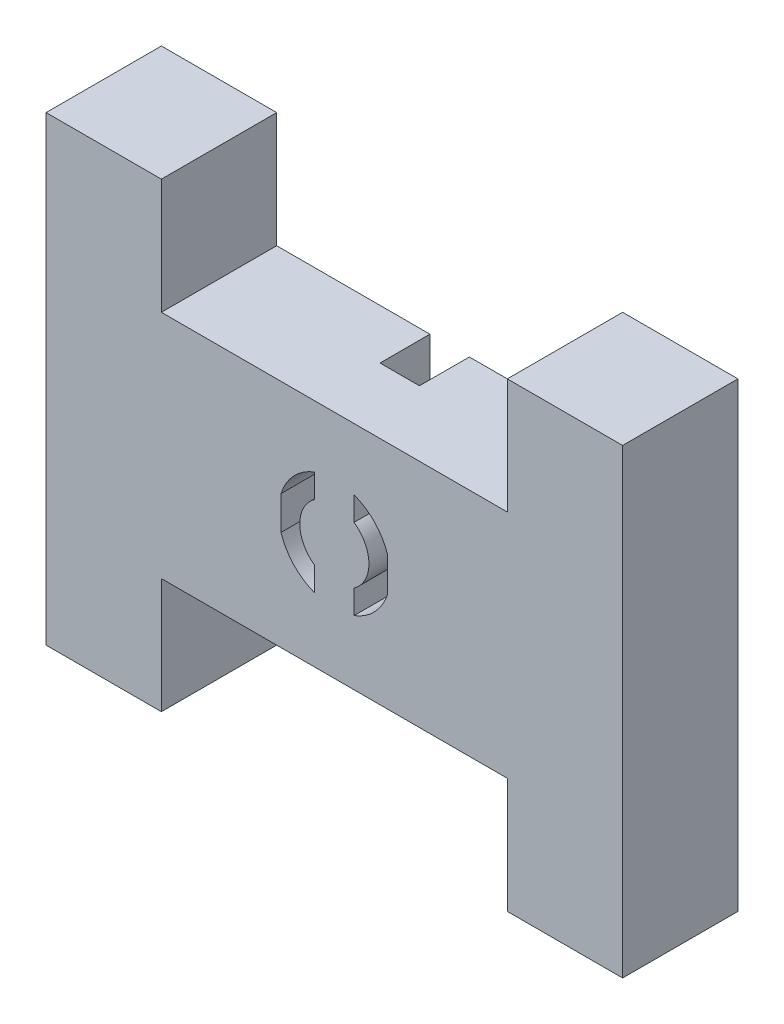
SolidWorks part; units mm, degrees
ref_plane "前视基准面" through (0, 0, 0) normal (0, 0, 1) x (1, 0, 0)
ref_plane "上视基准面" through (0, 0, 0) normal (0, 1, 0) x (1, 0, 0)
ref_plane "右视基准面" through (0, 0, 0) normal (1, 0, 0) x (0, 0, -1)
sketch "草图1" plane through (0, 0, 0) normal (0, 0, 1) x (1, 0, 0)
  line L1 (0, 0) -> (200, 0)
  line L2 (0, 0) -> (0, -200)
  line L3 (0, -200) -> (200, -200)
  line L4 (200, 0) -> (200, -200)
  dimension "D1" = 200
extrude "凸台-拉伸1" add sketch "草图1" along normal blind 100
sketch "草图2" plane through (0, 0, 0) normal (0, 0, -1) x (-1, 0, 0)
  line L0 (-146.25, -98.8742) -> (-146.25, -84.2732)
  line L1 (-146.25, -84.2732) -> (-146.25, -113.4751)
  line L2 (-100, 0) -> (-100, -98.8742) construction
  line L3 (-200, 0) -> (0, 0) construction
  line L4 (-53.75, -98.8742) -> (-146.25, -98.8742) construction
  line L5 (-53.75, -84.2732) -> (-53.75, -113.4751)
  circle A0 centre (-100, -98.8742) radius 48.5
  point P11 (0, 0)
  dimension "D1" = 97
  dimension "D2" = 92.5
extrude "切除-拉伸1" cut sketch "草图2" against normal blind 34.3 and the other way through all contours L5 A0 L0 L1
sketch "草图3" plane through (0, 0, 34.3) normal (0, 0, -1) x (-1, 0, 0)
  line L2 (-53.75, -113.4751) -> (-53.75, -84.2732)
  line L3 (-146.25, -84.2732) -> (-146.25, -113.4751)
  line L4 (-53.75, -113.4751) -> (-53.75, -84.2732)
  line L5 (-146.25, -84.2732) -> (-146.25, -113.4751)
  circle A0 centre (-100, -98.8742) radius 30
  arc A2 (-53.75, -84.2732) -> (-146.25, -84.2732) centre (-100, -98.8742) ccw
  arc A3 (-146.25, -113.4751) -> (-53.75, -113.4751) centre (-100, -98.8742) ccw
  arc A4 (-53.75, -84.2732) -> (-146.25, -84.2732) centre (-100, -98.8742) ccw
  arc A5 (-146.25, -113.4751) -> (-53.75, -113.4751) centre (-100, -98.8742) ccw
  dimension "D2" = 60
  dimension "D1" = 0
extrude "切除-拉伸2" cut sketch "草图3" against normal blind 9 contours A0
sketch "草图4" plane through (0, 0, 0) normal (0, 0, -1) x (-1, 0, 0)
  line L0 (0, -200) -> (-200, -200) construction
  line L1 (-117.1083, 2.2517) -> (-82.8917, 2.2517)
  line L2 (-117.1083, 2.2517) -> (-117.1083, -200)
  line L3 (-117.1083, -200) -> (-82.8917, -200)
  line L4 (-82.8917, 2.2517) -> (-82.8917, -200)
  line L5 (-117.1083, 2.2517) -> (-82.8917, -200) construction
  line L6 (-117.1083, -200) -> (-82.8917, 2.2517) construction
  circle A1 centre (-100, -98.8742) radius 30
  circle A2 centre (-100, -98.8742) radius 30
  point P9 (0, 0)
  line M3 (0, 0) -> (-200, 0)
  line M5 (-200, -200) -> (0, -200)
  arc M7 (-53.75, -113.4751) -> (-146.25, -113.4751) centre (-100, -98.8742) cw
  arc M9 (-146.25, -84.2732) -> (-53.75, -84.2732) centre (-100, -98.8742) cw
  dimension "D1" = 0
extrude "切除-拉伸3" cut sketch "草图4" against normal up to surface (43.3 mm away) contours L4 L2 M3 M9 | A2 L4 L2 M9 | L4 A2 L2 | A2 L2 L4 M7 | L4 L2 M7 M5 up to face at (70, -98.8742, 43.3)
sketch "草图6" plane through (0, 0, 100) normal (0, 0, 1) x (1, 0, 0)
  line L3 (82.8917, -74.2306) -> (82.8917, -53.4918)
  line L4 (0, 0) -> (0, -200)
  line L5 (0, -200) -> (200, -200)
  line L6 (200, -200) -> (200, 0)
  line L7 (200, 0) -> (0, 0)
  line L8 (0, 0) -> (0, -200)
  line L9 (0, -200) -> (200, -200)
  line L10 (200, -200) -> (200, 0)
  line L11 (200, 0) -> (0, 0)
  line L12 (82.8917, -144.2565) -> (82.8917, -123.5177)
  line L13 (53.75, -84.2732) -> (53.75, -113.4751)
  line L14 (82.8917, -74.2306) -> (82.8917, -53.4918)
  line L15 (82.8917, -144.2565) -> (82.8917, -123.5177)
  line L16 (53.75, -84.2732) -> (53.75, -113.4751)
  line L17 (117.1083, -53.4918) -> (117.1083, -74.2306)
  line L18 (146.25, -113.4751) -> (146.25, -84.2732)
  line L19 (117.1083, -123.5177) -> (117.1083, -144.2565)
  line L20 (117.1083, -53.4918) -> (117.1083, -74.2306)
  line L21 (146.25, -113.4751) -> (146.25, -84.2732)
  line L22 (117.1083, -123.5177) -> (117.1083, -144.2565)
  arc A3 (82.8917, -53.4918) -> (53.75, -84.2732) centre (100, -98.8742) ccw
  arc A4 (82.8917, -74.2306) -> (82.8917, -123.5177) centre (100, -98.8742) ccw
  arc A5 (53.75, -113.4751) -> (82.8917, -144.2565) centre (100, -98.8742) ccw
  arc A6 (82.8917, -53.4918) -> (53.75, -84.2732) centre (100, -98.8742) ccw
  arc A7 (82.8917, -74.2306) -> (82.8917, -123.5177) centre (100, -98.8742) ccw
  arc A8 (53.75, -113.4751) -> (82.8917, -144.2565) centre (100, -98.8742) ccw
  arc A9 (146.25, -84.2732) -> (117.1083, -53.4918) centre (100, -98.8742) ccw
  arc A10 (117.1083, -144.2565) -> (146.25, -113.4751) centre (100, -98.8742) ccw
  arc A11 (117.1083, -123.5177) -> (117.1083, -74.2306) centre (100, -98.8742) ccw
  arc A12 (146.25, -84.2732) -> (117.1083, -53.4918) centre (100, -98.8742) ccw
  arc A13 (117.1083, -144.2565) -> (146.25, -113.4751) centre (100, -98.8742) ccw
  arc A14 (117.1083, -123.5177) -> (117.1083, -74.2306) centre (100, -98.8742) ccw
  dimension "D1" = 0
  dimension "D2" = 0
  dimension "D3" = 0
extrude "切除-拉伸4" cut sketch "草图6" against normal blind 55 contours A6 L16 A8 L15 A7 L14 | L20 A14 L22 A13 L21 A12
sketch "草图7" plane through (0, 0, 34.3) normal (0, 0, -1) x (-1, 0, 0)
  line L6 (-117.1083, -74.2306) -> (-117.1083, -53.4918)
  line L7 (-146.25, -84.2732) -> (-146.25, -113.4751)
  line L8 (-117.1083, -144.2565) -> (-117.1083, -123.5177)
  line L9 (-117.1083, -74.2306) -> (-117.1083, -53.4918) construction
  line L10 (-146.25, -84.2732) -> (-146.25, -113.4751) construction
  line L11 (-117.1083, -144.2565) -> (-117.1083, -123.5177) construction
  circle A3 centre (-100, -98.8742) radius 42.5 construction
  circle A4 centre (-142.5, -98.8742) radius 1.75
  circle A5 centre (-130.052, -68.8221) radius 1.75
  arc A6 (-117.1083, -53.4918) -> (-146.25, -84.2732) centre (-100, -98.8742) ccw
  arc A7 (-146.25, -113.4751) -> (-117.1083, -144.2565) centre (-100, -98.8742) ccw
  arc A8 (-117.1083, -74.2306) -> (-117.1083, -123.5177) centre (-100, -98.8742) ccw
  arc A9 (-117.1083, -53.4918) -> (-146.25, -84.2732) centre (-100, -98.8742) ccw construction
  arc A10 (-146.25, -113.4751) -> (-117.1083, -144.2565) centre (-100, -98.8742) ccw construction
  arc A11 (-117.1083, -74.2306) -> (-117.1083, -123.5177) centre (-100, -98.8742) ccw construction
  circle A13 centre (-69.948, -68.8221) radius 1.75
  circle A14 centre (-57.5, -98.8742) radius 1.75
  circle A15 centre (-69.948, -128.9262) radius 1.75
  circle A17 centre (-130.052, -128.9262) radius 1.75
  circle A18 centre (-100, -56.3742) radius 1.75 [skipped]
  circle A19 centre (-100, -141.3742) radius 1.75 [skipped]
  point P29 (-100, -98.8742)
  dimension "D2" = 85
  dimension "D3" = 3.5
  dimension "D1" = 0
  dimension "D4" = 8
extrude "切除-拉伸7" cut sketch "草图7" against normal through all
sketch "草图9" plane through (0, 0, 0) normal (-1, 0, 0) x (0, 0, 1)
  line L4 (0, 0) -> (0, -200)
  line L5 (0, -200) -> (100, -200)
  line L6 (100, -200) -> (100, 0)
  line L7 (100, 0) -> (0, 0)
  line L8 (0, 0) -> (0, -200)
  line L9 (0, -200) -> (100, -200)
  line L10 (100, -200) -> (100, 0)
  line L11 (100, 0) -> (0, 0)
  dimension "D1" = 0
extrude "凸台-拉伸2" add sketch "草图9" along normal blind 150
sketch "草图10" plane through (200, 0, 0) normal (1, 0, 0) x (0, 0, -1)
  line L4 (0, -200) -> (0, 0)
  line L5 (0, 0) -> (-100, 0)
  line L6 (-100, 0) -> (-100, -200)
  line L7 (-100, -200) -> (0, -200)
  line L8 (0, -200) -> (0, 0)
  line L9 (0, 0) -> (-100, 0)
  line L10 (-100, 0) -> (-100, -200)
  line L11 (-100, -200) -> (0, -200)
  dimension "D1" = 0
extrude "凸台-拉伸3" add sketch "草图10" along normal blind 150
sketch "草图11" plane through (0, -200, 0) normal (0, -1, 0) x (1, 0, 0)
  line L0 (100, 43.3) -> (100, 150.463) construction
  line L1 (82.8917, 43.3) -> (117.1083, 43.3) construction
  line L2 (-150, 100) -> (350, 100) construction
  line L3 (-50, 100) -> (-150, 100)
  line L4 (-50, 100) -> (-50, 0)
  line L5 (-50, 0) -> (-150, 0)
  line L6 (-150, 100) -> (-150, 0)
  line L7 (250, 0) -> (350, 0)
  line L8 (350, 100) -> (350, 0)
  line L9 (250, 100) -> (350, 100)
  line L10 (250, 100) -> (250, 0)
  dimension "D1" = 100
extrude "凸台-拉伸4" add sketch "草图11" along normal blind 100
sketch "草图12" plane through (0, 0, 0) normal (0, 1, 0) x (1, 0, 0)
  line L0 (250, -100) -> (250, 0) construction
  line L1 (250, 0) -> (350, 0) construction
  line L2 (350, 0) -> (350, -100) construction
  line L3 (350, -100) -> (250, -100) construction
  line L4 (-50, 0) -> (-50, -100) construction
  line L5 (-50, -100) -> (-150, -100) construction
  line L6 (-150, -100) -> (-150, 0) construction
  line L7 (-150, 0) -> (-50, 0) construction
  line L8 (250, -100) -> (250, 0)
  line L9 (250, 0) -> (350, 0)
  line L10 (350, 0) -> (350, -100)
  line L11 (350, -100) -> (250, -100)
  line L12 (-50, 0) -> (-50, -100)
  line L13 (-50, -100) -> (-150, -100)
  line L14 (-150, -100) -> (-150, 0)
  line L15 (-150, 0) -> (-50, 0)
extrude "凸台-拉伸5" add sketch "草图12" along normal blind 100
